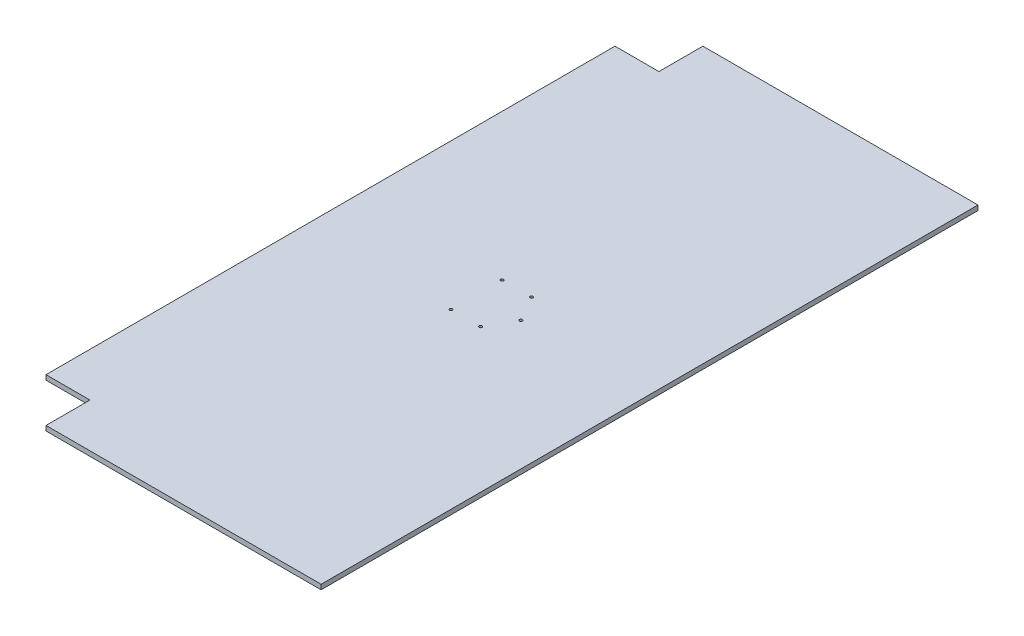
SolidWorks part; units mm, degrees
ref_plane "Front Plane" through (0, 0, 0) normal (0, 0, 1) x (1, 0, 0)
ref_plane "Top Plane" through (0, 0, 0) normal (0, 1, 0) x (1, 0, 0)
ref_plane "Right Plane" through (0, 0, 0) normal (1, 0, 0) x (0, 0, -1)
sketch "Sketch1" plane through (0, 0, 0) normal (0, 1, 0) x (1, 0, 0)
  line L5 (-304.5, -612.5) -> (304.5, -612.5)
  line L6 (-304.5, -612.5) -> (-304.5, 612.5)
  line L7 (-304.5, 612.5) -> (304.5, 612.5)
  line L14 (304.5, -612.5) -> (304.5, 612.5)
  line L15 (-304.5, -612.5) -> (304.5, 612.5) construction
  line L16 (-304.5, 612.5) -> (304.5, -612.5) construction
  line L17 (304.5, 612.5) -> (224.5, 612.5)
  line L18 (304.5, 612.5) -> (304.5, 497.5)
  line L21 (-304.5, 612.5) -> (-845.5, 612.5)
  line L22 (-304.5, 612.5) -> (-304.5, 497.5)
  line L26 (-304.5, -532.5) -> (-304.5, -612.5)
  line L27 (-304.5, -612.5) -> (-845.5, -612.5)
  line L29 (304.5, -612.5) -> (224.5, -612.5)
  line L30 (304.5, -612.5) -> (304.5, -532.5)
  point P0 (0, 0)
  dimension "D1" = 609
  dimension "D2" = 1225
extrude "Boss-Extrude1" add sketch "Sketch1" along normal blind 9
sketch "Sketch2" plane through (0, 9, 0) normal (0, 1, 0) x (1, 0, 0)
  line L0 (304.5, -612.5) -> (304.5, 612.5) construction
  line L1 (304.5, -612.5) -> (304.5, 612.5)
  line L2 (290.5, 612.5) -> (290.5, -612.5)
  line L4 (290.5, -612.5) -> (803.5, -612.5)
  line L5 (885.5, -530.5) -> (885.5, 533)
  line L6 (803.5, 612.5) -> (290.5, 612.5)
  line L7 (803.5, -612.5) -> (803.5, -530.5)
  line L8 (290.5, -612.5) -> (803.5, -612.5)
  line L9 (885.5, -530.5) -> (885.5, 533)
  line L10 (803.5, 612.5) -> (290.5, 612.5)
  line L23 (803.5, -612.5) -> (803.5, -530.5)
  line L24 (803.5, -530.5) -> (885.5, -530.5)
  line L25 (803.5, -530.5) -> (885.5, -530.5)
  line L26 (885.5, 533) -> (803.5, 533)
  line L27 (885.5, 533) -> (803.5, 533)
  line L28 (803.5, 533) -> (803.5, 612.5)
  line L29 (803.5, 533) -> (803.5, 612.5)
  line L30 (290.5, 612.5) -> (290.5, -612.5)
  line L31 (290.5, 612.5) -> (290.5, -612.5)
  line M5 (-304.5, -612.5) -> (304.5, -612.5)
  line M6 (304.5, -612.5) -> (304.5, 612.5)
  line M7 (304.5, 612.5) -> (-304.5, 612.5)
  dimension "D1" = 0
extrude "Cut-Extrude1" cut sketch "Sketch2" against normal blind 10 contours L2 M7 M5 M6
sketch "Sketch3" plane through (0, 9, 0) normal (0, 1, 0) x (1, 0, 0)
  line L7 (-304.5, 612.5) -> (-222.5, 612.5)
  line L8 (-304.5, 612.5) -> (-304.5, 530.5)
  line L9 (-304.5, 530.5) -> (-222.5, 530.5)
  line L10 (-222.5, 612.5) -> (-222.5, 530.5)
  line L12 (-304.5, -612.5) -> (-222.5, -612.5)
  line L13 (-304.5, -612.5) -> (-304.5, -530.5)
  line L14 (-304.5, -530.5) -> (-222.5, -530.5)
  line L15 (-222.5, -612.5) -> (-222.5, -530.5)
  dimension "D1" = 82
  dimension "D2" = 82
  dimension "D3" = 82
  dimension "D4" = 82
extrude "Cut-Extrude5" cut sketch "Sketch3" against normal blind 10
sketch "Sketch4" plane through (0, 9, 0) normal (0, 1, 0) x (1, 0, 0)
  circle A0 centre (23, 47.6314) radius 2.75 construction
  circle A1 centre (23, 47.6314) radius 2.75
  circle A2 centre (-32, -47.6314) radius 2.75 construction
  circle A3 centre (23, -47.6314) radius 2.75 construction
  circle A4 centre (-32, -47.6314) radius 2.75
  circle A5 centre (23, -47.6314) radius 2.75
  circle A6 centre (50.5, 0) radius 2.75 construction
  circle A7 centre (50.5, 0) radius 2.75
  circle A8 centre (-32, 47.6314) radius 2.75 construction
  circle A9 centre (-32, 47.6314) radius 2.75
extrude "Cut-Extrude6" cut sketch "Sketch4" against normal blind 10
